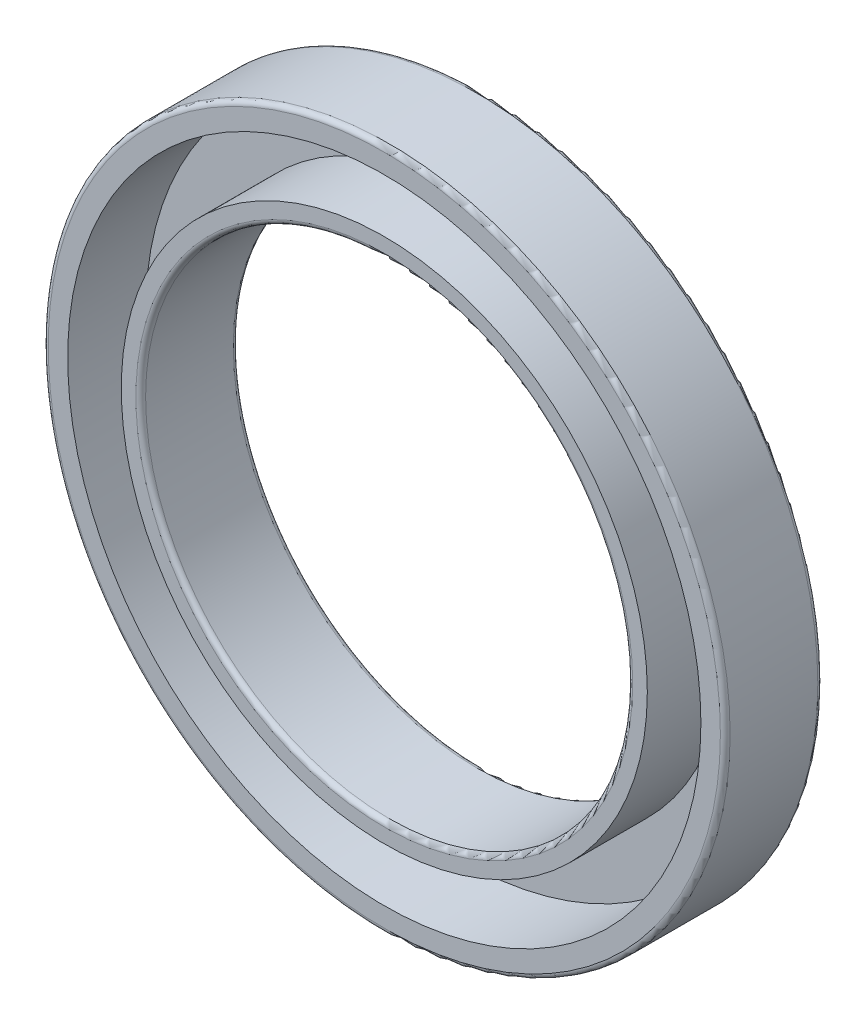
SolidWorks part; units mm, degrees
ref_plane "Front Plane" through (0, 0, 0) normal (0, 0, 1) x (1, 0, 0)
ref_plane "Top Plane" through (0, 0, 0) normal (0, 1, 0) x (1, 0, 0)
ref_plane "Right Plane" through (0, 0, 0) normal (1, 0, 0) x (0, 0, -1)
sketch "Sketch1" plane through (0, 0, 0) normal (0, 0, 1) x (1, 0, 0)
  circle A0 centre (0, 0) radius 35
  circle A1 centre (0, 0) radius 25
  dimension "D1" = 50
  dimension "D2" = 70
extrude "Boss-Extrude1" add sketch "Sketch1" along normal blind 10
sketch "Sketch2" plane through (0, 0, 10) normal (0, 0, 1) x (1, 0, 0)
  circle A0 centre (0, 0) radius 27
  circle A1 centre (0, 0) radius 32.5
  dimension "D1" = 54
  dimension "D2" = 65
extrude "Cut-Extrude1" cut sketch "Sketch2" against normal blind 8
fillet "Fillet1" radius 0.5 4 edges at (25, 0, 0) (25, 0, 10) (35, 0, 10) (35, 0, 0)
